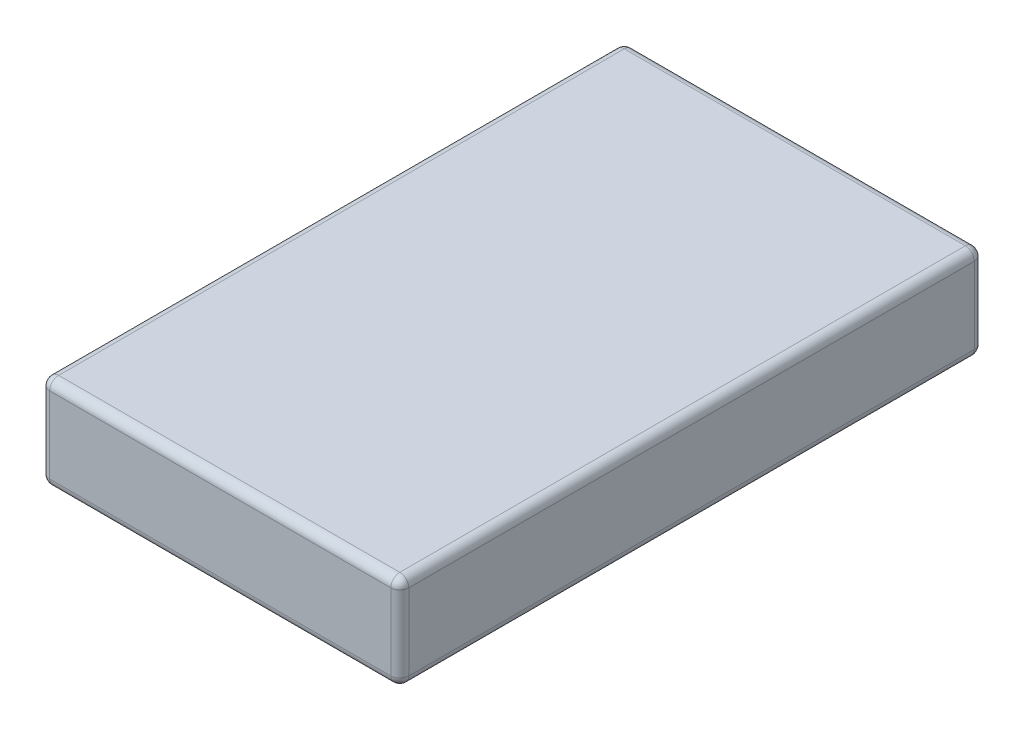
SolidWorks part; units mm, degrees
ref_plane "Front Plane" through (0, 0, 0) normal (0, 0, 1) x (1, 0, 0)
ref_plane "Top Plane" through (0, 0, 0) normal (0, 1, 0) x (1, 0, 0)
ref_plane "Right Plane" through (0, 0, 0) normal (1, 0, 0) x (0, 0, -1)
sketch "Sketch1" plane through (0, 0, 0) normal (0, 1, 0) x (1, 0, 0)
  line L1 (-1016, 1651) -> (1016, 1651)
  line L2 (-1016, 1651) -> (-1016, -1651)
  line L3 (-1016, -1651) -> (1016, -1651)
  line L4 (1016, 1651) -> (1016, -1651)
  line L5 (-1016, 1651) -> (1016, -1651) construction
  line L6 (-1016, -1651) -> (1016, 1651) construction
  point P0 (0, 0)
  dimension "D1" = 3302
  dimension "D2" = 2032
extrude "Boss-Extrude1" add sketch "Sketch1" along normal blind 533.4
fillet "Fillet1" radius 50.8 12 edges at (-1016, 266.7, -1651) (1016, 266.7, -1651) (-1016, 266.7, 1651) (1016, 266.7, 1651) (0, 0, -1651) (-1016, 0, 0) (0, 0, 1651) (1016, 0, 0) (0, 533.4, 1651) (-1016, 533.4, 0) (0, 533.4, -1651) (1016, 533.4, 0)
